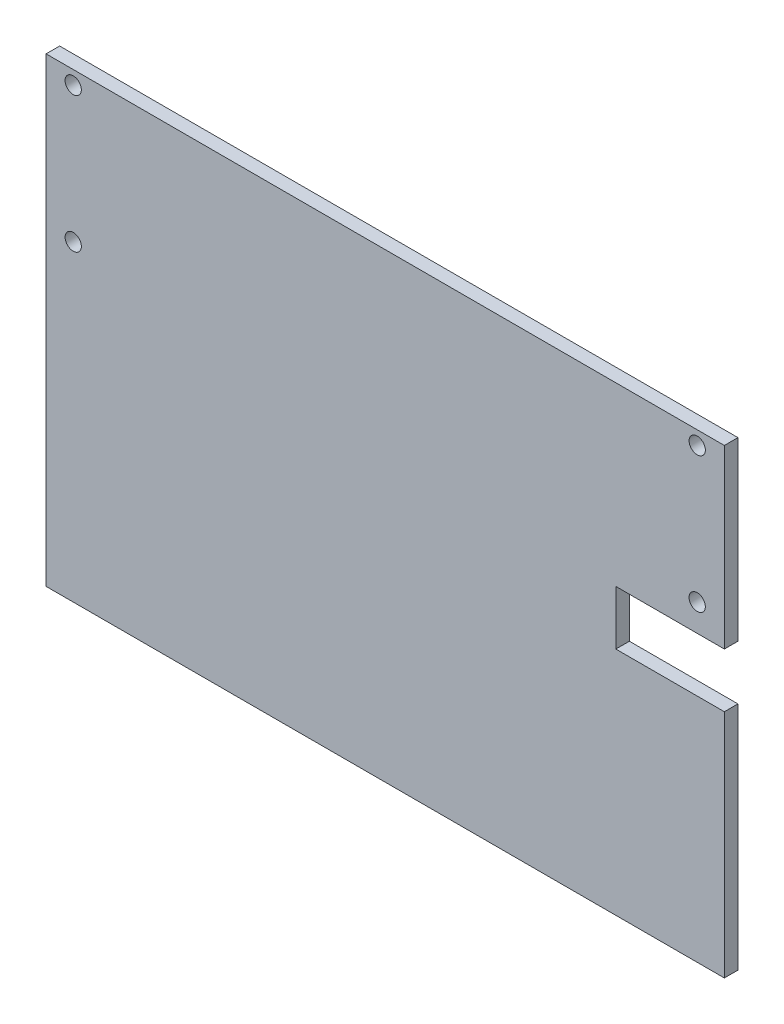
SolidWorks part; units mm, degrees
ref_plane "Plan de face" through (0, 0, 0) normal (0, 0, 1) x (1, 0, 0)
ref_plane "Plan de dessus" through (0, 0, 0) normal (0, 1, 0) x (1, 0, 0)
ref_plane "Plan de droite" through (0, 0, 0) normal (1, 0, 0) x (0, 0, -1)
sketch "Esquisse1" plane through (0, 0, 0) normal (0, 0, 1) x (1, 0, 0)
  line L0 (125, 0) -> (125, -170) construction
  line L1 (0, 0) -> (250, 0)
  line L2 (0, 0) -> (0, -170)
  line L3 (0, -170) -> (250, -170)
  line L4 (250, 0) -> (250, -170)
  circle A0 centre (10, -55) radius 3
  circle A3 centre (10, -5) radius 3
  circle A4 centre (240, -55) radius 3
  circle A5 centre (240, -5) radius 3
  dimension "D3" = 6
  dimension "D4" = 6
  dimension "D5" = 10
  dimension "D6" = 115
  dimension "D1" = 250
  dimension "D2" = 170
  dimension "D7" = 10
  dimension "D8" = 5
extrude "Boss.-Extru.1" add sketch "Esquisse1" along normal blind 5
sketch "Esquisse4" plane through (0, 0, 5) normal (0, 0, 1) x (1, 0, 0)
  line L0 (250, -65) -> (210, -65)
  line L1 (250, -170) -> (250, 0) construction
  line L2 (210, -65) -> (210, -85)
  line L3 (210, -85) -> (250, -85)
  line L4 (250, -85) -> (250, -65)
  line L6 (0, -170) -> (250, -170) construction
  dimension "D1" = 85
  dimension "D2" = 40
  dimension "D3" = 20
extrude "Enlèv. mat.-Extru.1" cut sketch "Esquisse4" against normal blind 10
